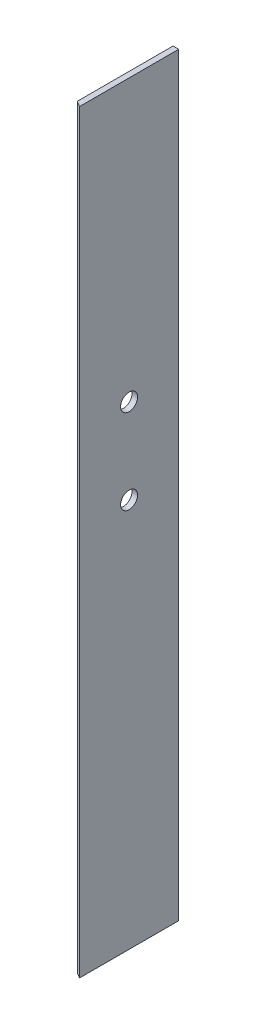
SolidWorks part; units mm, degrees
ref_plane "Спереди" through (0, 0, 0) normal (0, 0, 1) x (1, 0, 0)
ref_plane "Сверху" through (0, 0, 0) normal (0, 1, 0) x (1, 0, 0)
ref_plane "Справа" through (0, 0, 0) normal (1, 0, 0) x (0, 0, -1)
sketch "Эскиз1" plane through (0, 0, 0) normal (0, 1, 0) x (1, 0, 0)
  line L1 (1, 0) -> (5, 0)
  line L2 (1, 0) -> (1, -67.636)
  line L3 (1, -67.636) -> (5, -70.0688)
  line L4 (5, 0) -> (5, -70.0688)
  line L6 (5, -70.2138) -> (5, 227.4589) construction
  dimension "D1" = 4
extrude "Вытянуть1" add sketch "Эскиз1" along normal up to surface (533.2137 mm away)
sketch "Sketch1" plane through (5, 0, 0) normal (1, 0, 0) x (0, 0, -1)
  line L0 (-35.0344, 481.4479) -> (-35.0344, 379.7999) construction
  line L2 (-70.0688, 0) -> (0, 0) construction
  circle A0 centre (-35.0344, 335) radius 6
  circle A1 centre (-35.0344, 275) radius 6
  dimension "D1" = 275
  dimension "D2" = 335
extrude "Cut-Extrude1" cut sketch "Sketch1" against normal through all
